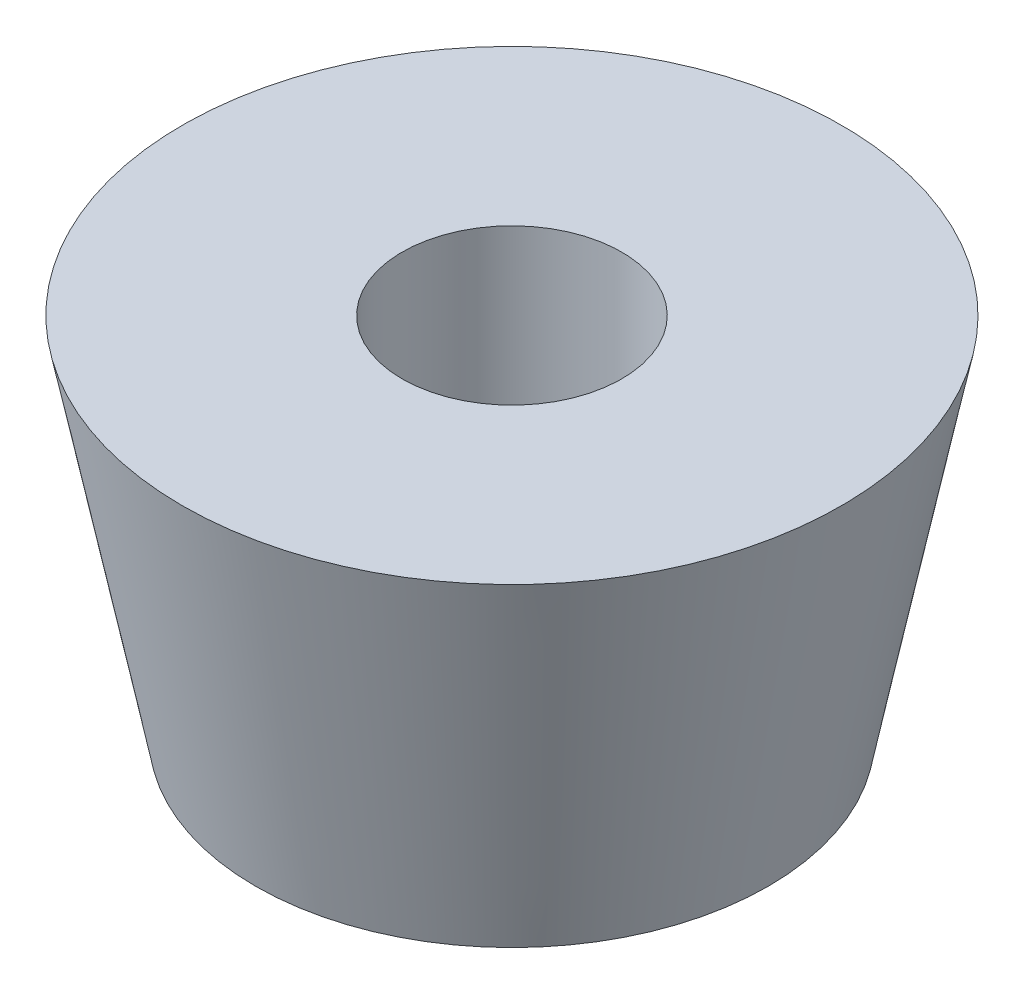
SolidWorks part; units mm, degrees
ref_plane "Ebene vorne" through (0, 0, 0) normal (0, 0, 1) x (1, 0, 0)
ref_plane "Ebene oben" through (0, 0, 0) normal (0, 1, 0) x (1, 0, 0)
ref_plane "Ebene rechts" through (0, 0, 0) normal (1, 0, 0) x (0, 0, -1)
sketch "Sketch1" plane through (0, 0, 0) normal (1, 0, 0) x (0, 0, -1)
  line L0 (1.5, 0) -> (1.5, -5)
  line L1 (1.5, -5) -> (3.5, -5)
  line L2 (3.5, -5) -> (4.5, 0)
  line L3 (4.5, 0) -> (1.5, 0)
  line L4 (0, 0) -> (0, -7.739) construction
  point P7 (0, 0)
  dimension "D1" = 5
  dimension "D2" = 3
  dimension "D3" = 2
  dimension "D4" = 1.5
revolve "Revolve1" add sketch "Sketch1" angle 360 about L4
